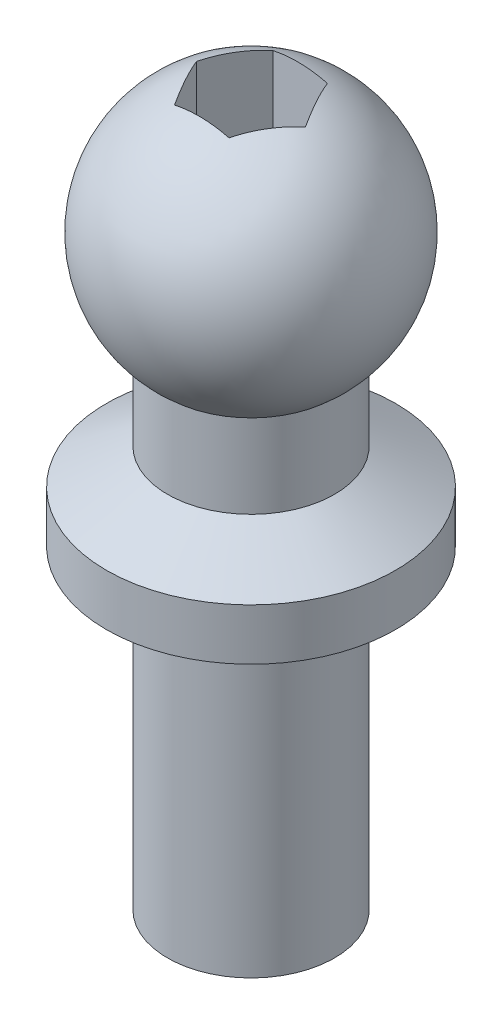
SolidWorks part; units mm, degrees
ref_plane "Piano frontale" through (0, 0, 0) normal (0, 0, 1) x (1, 0, 0)
ref_plane "Piano superiore" through (0, 0, 0) normal (0, 1, 0) x (1, 0, 0)
ref_plane "Piano destro" through (0, 0, 0) normal (1, 0, 0) x (0, 0, -1)
sketch "Schizzo1" plane through (0, 0, 0) normal (0, 0, 1) x (1, 0, 0)
  line L0 (0, 0) -> (0, 11.1836) construction
  line L1 (0, 0) -> (1.3, 0)
  line L2 (1.3, 0) -> (1.3, 4.9)
  line L3 (1.3, 4.9) -> (2.25, 4.9)
  line L4 (2.25, 4.9) -> (2.25, 5.7)
  line L5 (2.25, 5.7) -> (1.3, 6.2485)
  line L6 (1.3, 6.2485) -> (1.3, 7.5485)
  line L7 (0, 0) -> (0, 11.1836)
  arc A0 (1.3, 7.5485) -> (0, 11.1836) centre (0, 9.1336) ccw
  dimension "D7" = 4.1
  dimension "D1" = 2.6
  dimension "D2" = 4.9
  dimension "D3" = 0.8
  dimension "D4" = 30
  dimension "D5" = 4.5
  dimension "D6" = 2.6
  dimension "D8" = 1.3
revolve "Rivoluzione1" add sketch "Schizzo1" angle 360 about L0
cosmetic thread "Filettatura cosmetica1" parameters "D2"=2.016
ref_plane "Piano1" through (0, 11.09, 0) normal (0, -1, 0) x (-1, 0, 0)
other "TaglioSuperficie1"
sketch "Schizzo2" plane through (0, 11.09, 0) normal (0, -1, 0) x (-1, 0, 0)
  line L1 (-0.4163, -0.7594) -> (0.4495, -0.7402)
  line L2 (0.4495, -0.7402) -> (0.8658, 0.0191)
  line L3 (0.8658, 0.0191) -> (0.4163, 0.7594)
  line L4 (0.4163, 0.7594) -> (-0.4495, 0.7402)
  line L5 (-0.4495, 0.7402) -> (-0.8658, -0.0191)
  line L6 (-0.8658, -0.0191) -> (-0.4163, -0.7594)
  circle A0 centre (0, 0) radius 0.866 construction
  dimension "D1" = 1.5
extrude "Taglio-Estrusione1" cut sketch "Schizzo2" along normal blind 1.5
